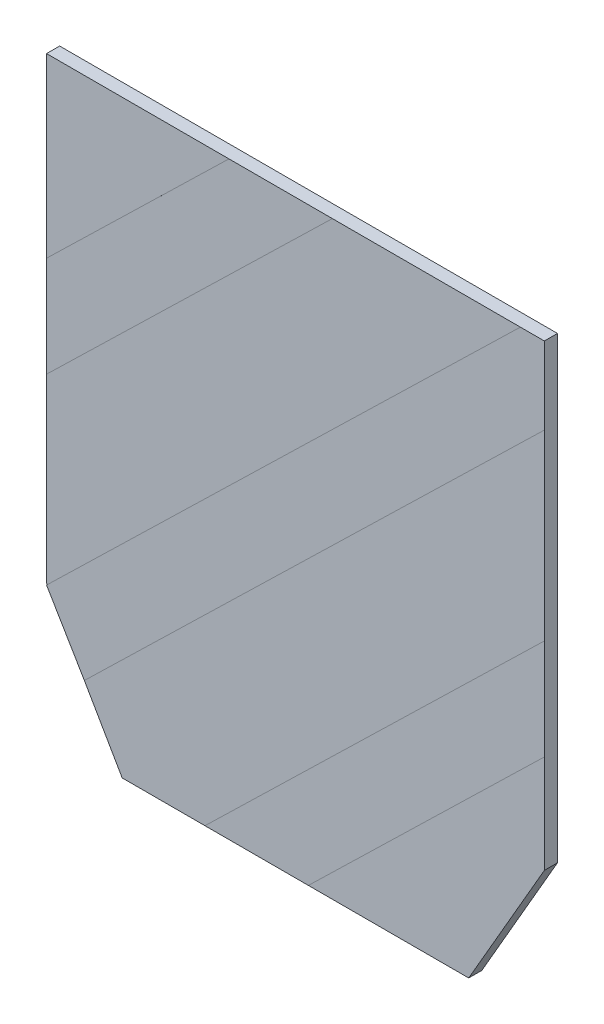
SolidWorks part; units mm, degrees
ref_plane "Front Plane" through (0, 0, 0) normal (0, 0, 1) x (1, 0, 0)
ref_plane "Top Plane" through (0, 0, 0) normal (0, 1, 0) x (1, 0, 0)
ref_plane "Right Plane" through (0, 0, 0) normal (1, 0, 0) x (0, 0, -1)
sketch "Sketch1" plane through (0, 0, 0) normal (0, 0, 1) x (1, 0, 0)
  line L0 (-38, -35) -> (-26.453, -55)
  line L2 (-38, -35) -> (-38, 35)
  line L3 (-38, 35) -> (38, 35)
  line L4 (38, -35) -> (38, 35)
  line L5 (-38, -35) -> (38, 35) construction
  line L6 (-38, 35) -> (38, -35) construction
  line L7 (-26.453, -55) -> (26.453, -55)
  line L8 (26.453, -55) -> (38, -35)
  point P0 (0, 0)
  point P6 (0, -55)
  dimension "D1" = 60
  dimension "D2" = 60
  dimension "D3" = 76
  dimension "D4" = 20
  dimension "D5" = 90
extrude "Boss-Extrude1" add sketch "Sketch1" along normal blind 2
sketch "Sketch2" plane through (0, 0, 2) normal (0, 0, 1) x (1, 0, 0)
  line L0 (-38, 7.9455) -> (-10.1491, 35)
  line L1 (-38, 35) -> (-38, -35) construction
  line L2 (38, 35) -> (-38, 35) construction
  line L3 (-38, -7.3901) -> (5.6379, 35)
  line L4 (-38, -35.2729) -> (34.3415, 35)
  line L5 (-32.2265, -45) -> (38, 23.2183)
  line L6 (-38, -35) -> (-26.453, -55) construction
  line L7 (38, -35) -> (38, 35) construction
  line L8 (-13.8173, -55) -> (38, -4.6645)
  line L9 (1.9697, -55) -> (38, -20)
  line L10 (-26.453, -55) -> (26.453, -55) construction
  line L11 (38, -35) -> (38, -55) construction
  line L12 (38, -55) -> (26.453, -55) construction
  line L13 (-10.1491, 35) -> (5.6379, 35)
  line L14 (-38, 7.9455) -> (-38, -7.3901)
  line L15 (-13.8173, -55) -> (1.9697, -55)
  line L16 (38, -4.6645) -> (38, -20)
  line L17 (34.3415, 35) -> (38, 35)
  line L18 (38, 35) -> (38, 23.2183)
  line L19 (-38, -35.2729) -> (-32.2265, -45)
  dimension "D1" = 11
  dimension "D2" = 11
  dimension "D3" = 11
  dimension "D4" = 20
  dimension "D5" = 20
  dimension "D6" = 35
extrude "Boss-Extrude2" add sketch "Sketch2" along normal blind 0.0001
